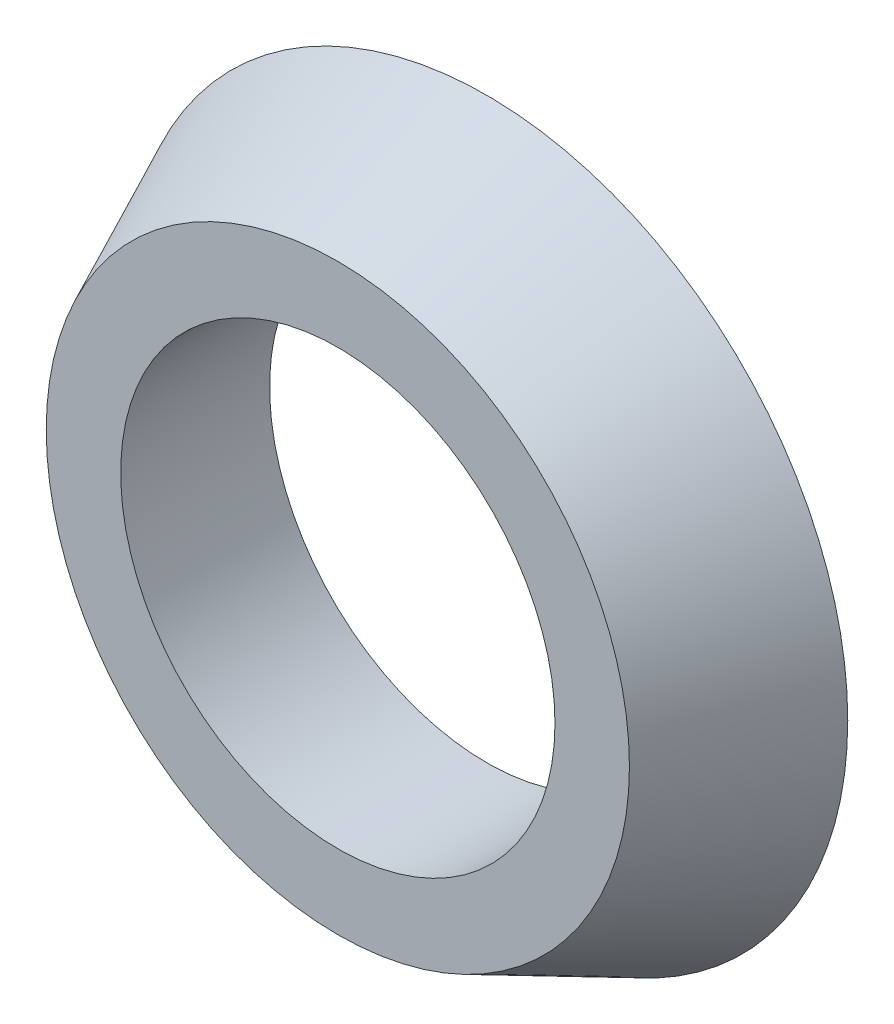
SolidWorks part; units mm, degrees
ref_plane "Front Plane" through (0, 0, 0) normal (0, 0, 1) x (1, 0, 0)
ref_plane "Top Plane" through (0, 0, 0) normal (0, 1, 0) x (1, 0, 0)
ref_plane "Right Plane" through (0, 0, 0) normal (1, 0, 0) x (0, 0, -1)
sketch "Sketch1" plane through (0, 0, 0) normal (0, 0, 1) x (1, 0, 0)
  circle A0 centre (0, 0) radius 23.5
  dimension "D2" = 47
extrude "Boss-Extrude1" add sketch "Sketch1" against normal blind 12 draft 25 draft outward yes
sketch "Sketch2" plane through (0, 0, 0) normal (0, 0, 1) x (1, 0, 0)
  circle A0 centre (0, 0) radius 17.5
  dimension "D1" = 35
extrude "Cut-Extrude1" cut sketch "Sketch2" against normal up to next
